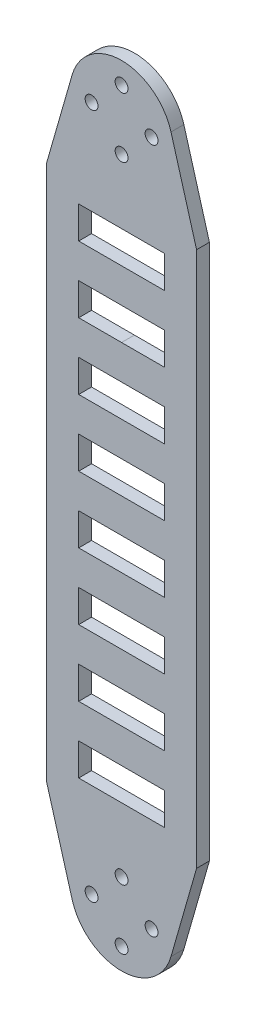
SolidWorks part; units mm, degrees
ref_plane "Front Plane" through (0, 0, 0) normal (0, 0, 1) x (1, 0, 0)
ref_plane "Top Plane" through (0, 0, 0) normal (0, 1, 0) x (1, 0, 0)
ref_plane "Right Plane" through (0, 0, 0) normal (1, 0, 0) x (0, 0, -1)
sketch "Sketch1" plane through (0, 0, 0) normal (0, 0, 1) x (1, 0, 0)
  line L0 (-12, 0) -> (12, 0) construction
  line L1 (-12, 0) -> (-12, 160) construction
  line L2 (12, 0) -> (12, 160) construction
  line L3 (-12, 160) -> (12, 160) construction
  line L4 (-12, 80) -> (12, 80)
  line L5 (-10, 22) -> (10, 22)
  line L6 (-10, 22) -> (-10, 29.5)
  line L7 (-10, 29.5) -> (10, 29.5)
  line L8 (10, 22) -> (10, 29.5)
  line L9 (-10, 22) -> (10, 29.5) construction
  line L10 (-10, 29.5) -> (10, 22) construction
  line L11 (0, 0) -> (0, 160)
  line L12 (-10, 37.5) -> (-10, 45)
  line L13 (-10, 37.5) -> (10, 37.5)
  line L14 (10, 37.5) -> (10, 45)
  line L15 (-10, 45) -> (10, 45)
  line L16 (-10, 53) -> (-10, 60.5)
  line L17 (-10, 53) -> (10, 53)
  line L18 (10, 53) -> (10, 60.5)
  line L19 (-10, 60.5) -> (10, 60.5)
  line L20 (-10, 68.5) -> (-10, 76)
  line L21 (-10, 68.5) -> (10, 68.5)
  line L22 (10, 68.5) -> (10, 76)
  line L23 (-10, 76) -> (10, 76)
  line L24 (-10, 84) -> (-10, 91.5)
  line L25 (-10, 84) -> (10, 84)
  line L26 (10, 84) -> (10, 91.5)
  line L27 (-10, 91.5) -> (10, 91.5)
  line L28 (-10, 99.5) -> (-10, 107)
  line L29 (-10, 99.5) -> (10, 99.5)
  line L30 (10, 99.5) -> (10, 107)
  line L31 (-10, 107) -> (10, 107)
  line L32 (-10, 115) -> (-10, 122.5)
  line L33 (-10, 115) -> (10, 115)
  line L34 (10, 115) -> (10, 122.5)
  line L35 (-10, 122.5) -> (10, 122.5)
  line L36 (-10, 130.5) -> (-10, 138)
  line L37 (-10, 130.5) -> (10, 130.5)
  line L38 (10, 130.5) -> (10, 138)
  line L39 (-10, 138) -> (10, 138)
  line L40 (-17.5, 142.5) -> (-11.5354, 163.3068)
  line L41 (17.5, 17.5) -> (-17.5, 17.5)
  line L42 (17.5, 17.5) -> (17.5, 142.5)
  line L43 (17.5, 142.5) -> (-17.5, 142.5)
  line L44 (-17.5, 17.5) -> (-17.5, 142.5)
  line L45 (17.5, 17.5) -> (-17.5, 142.5) construction
  line L46 (17.5, 142.5) -> (-17.5, 17.5) construction
  line L47 (17.5, 142.5) -> (11.5354, 163.3068)
  line L48 (17.5, 17.5) -> (11.5354, -3.3068)
  line L49 (-17.5, 17.5) -> (-11.5354, -3.3068)
  circle A0 centre (0, 0) radius 12
  circle A1 centre (0, -7) radius 1.5
  circle A2 centre (7, 0) radius 1.5
  circle A3 centre (0, 7) radius 1.5
  circle A4 centre (-7, 0) radius 1.5
  circle A5 centre (0, 160) radius 12
  circle A6 centre (7, 160) radius 1.5
  circle A7 centre (0, 153) radius 1.5
  circle A8 centre (-7, 160) radius 1.5
  circle A9 centre (0, 167) radius 1.5
  point P14 (0, 0)
  point P18 (0, 80)
  point P29 (0, 160)
  point P30 (0, 25.75)
  point P35 (-12, 80)
  point P68 (-11.625, 162.9765)
  dimension "D1" = 24
  dimension "D2" = 3
  dimension "D6" = 3
  dimension "D9" = 20
  dimension "D4" = 7
  dimension "D5" = 160
  dimension "D8" = 7
  dimension "D10" = 7.5
  dimension "D12" = 4
  dimension "D13" = 8
  dimension "D14" = 35
  dimension "D15" = 125
  dimension "D11" = 8
  dimension "D3" = 4
  dimension "D7" = 4
extrude "Boss-Extrude4" add sketch "Sketch1" along normal blind 3
